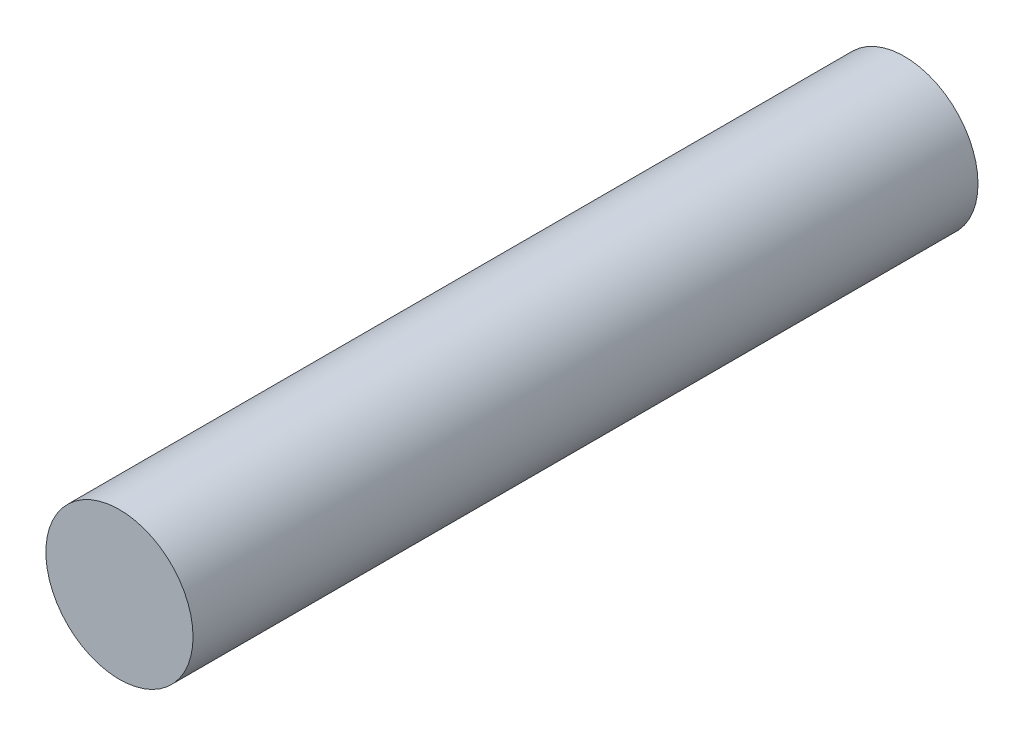
SolidWorks part; units mm, degrees
ref_plane "Front Plane" through (0, 0, 0) normal (0, 0, 1) x (1, 0, 0)
ref_plane "Top Plane" through (0, 0, 0) normal (0, 1, 0) x (1, 0, 0)
ref_plane "Right Plane" through (0, 0, 0) normal (1, 0, 0) x (0, 0, -1)
sketch "Sketch1" plane through (0, 0, 0) normal (0, 0, 1) x (1, 0, 0)
  circle A0 centre (0, 0) radius 38.1
  dimension "D1" = 76.2
extrude "Boss-Extrude1" add sketch "Sketch1" along normal mid plane 406.4
